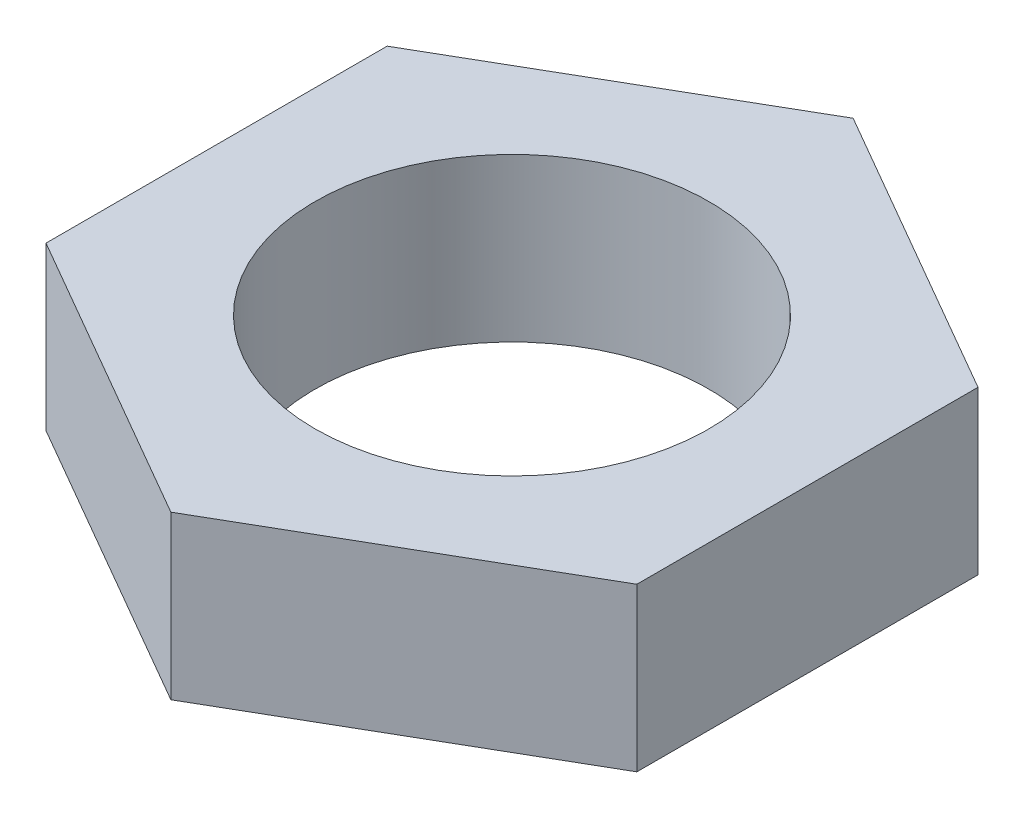
SolidWorks part; units mm, degrees
ref_plane "Alzado" through (0, 0, 0) normal (0, 0, 1) x (1, 0, 0)
ref_plane "Planta" through (0, 0, 0) normal (0, 1, 0) x (1, 0, 0)
ref_plane "Vista lateral" through (0, 0, 0) normal (1, 0, 0) x (0, 0, -1)
sketch "Croquis1" plane through (0, 0, 0) normal (0, 1, 0) x (1, 0, 0)
  line L0 (0, 0) -> (0, 17.3732) construction
  line L1 (6, -3.4641) -> (6, 3.4641)
  line L2 (6, 3.4641) -> (0, 6.9282)
  line L3 (0, 6.9282) -> (-6, 3.4641)
  line L4 (-6, 3.4641) -> (-6, -3.4641)
  line L5 (-6, -3.4641) -> (0, -6.9282)
  line L6 (0, -6.9282) -> (6, -3.4641)
  circle A0 centre (0, 0) radius 6 construction
  circle A1 centre (0, 0) radius 4
  dimension "D2" = 8
  dimension "D1" = 12
extrude "Saliente-Extruir1" add sketch "Croquis1" along normal blind 3.3
